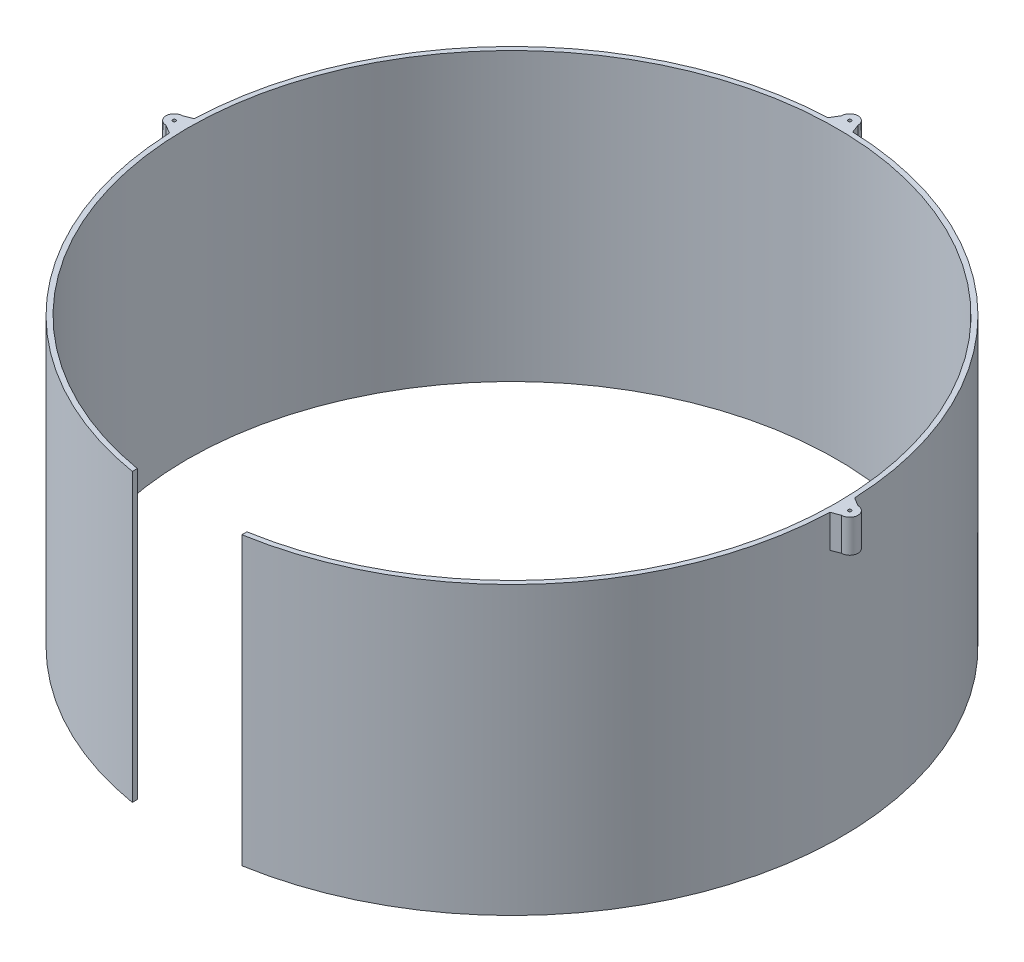
SolidWorks part; units mm, degrees
ref_plane "Front Plane" through (0, 0, 0) normal (0, 0, 1) x (1, 0, 0)
ref_plane "Top Plane" through (0, 0, 0) normal (0, 1, 0) x (1, 0, 0)
ref_plane "Right Plane" through (0, 0, 0) normal (1, 0, 0) x (0, 0, -1)
sketch "Sketch1" plane through (0, 0, 0) normal (0, 1, 0) x (1, 0, 0)
  line L0 (-16.6343, -97.0853) -> (-16.6343, -98.6068)
  line L1 (16.6343, -97.0853) -> (16.6343, -98.6068)
  line L2 (-16.6343, -97.0853) -> (16.6343, -97.0853) construction
  arc A0 (16.6343, -98.6068) -> (-16.6343, -98.6068) centre (0, 0) ccw
  arc A1 (16.6343, -97.0853) -> (-16.6343, -97.0853) centre (0, 0) ccw
  point P5 (0, -97.0853)
  dimension "D1" = 197
extrude "Boss-Extrude1" add sketch "Sketch1" along normal blind 87
sketch "Sketch3" plane through (0, 87, 0) normal (0, 1, 0) x (1, 0, 0)
  line L0 (-102.5, -2.5) -> (-99.3364, -4.4009)
  line L1 (-102.5, 2.5) -> (-99.1855, 3.7708)
  line L2 (-99.1855, 3.7708) -> (-99.3364, -4.4009)
  line L3 (-2.5, 102.5) -> (-4.4009, 99.3364)
  line L4 (2.5, 102.5) -> (3.7708, 99.1855)
  line L5 (3.7708, 99.1855) -> (-4.4009, 99.3364)
  line L6 (102.5, 2.5) -> (99.3364, 4.4009)
  line L7 (102.5, -2.5) -> (99.1855, -3.7708)
  line L8 (99.1855, -3.7708) -> (99.3364, 4.4009)
  circle A0 centre (-102.5, 0) radius 0.5
  circle A1 centre (0, 0) radius 102.5 construction
  arc A2 (102.5, -2.5) -> (102.5, 2.5) centre (102.5, 0) ccw
  arc A3 (-102.5, 2.5) -> (-102.5, -2.5) centre (-102.5, 0) ccw
  arc A4 (2.5, 102.5) -> (-2.5, 102.5) centre (0, 102.5) ccw
  circle A5 centre (0, 102.5) radius 0.5
  circle A6 centre (102.5, 0) radius 0.5
  dimension "D1" = 205
  dimension "D2" = 5
  dimension "D3" = 5
  dimension "D4" = 5
  dimension "D5" = 1
  dimension "D6" = 1
  dimension "D7" = 1
extrude "Boss-Extrude2" add sketch "Sketch3" against normal blind 10
